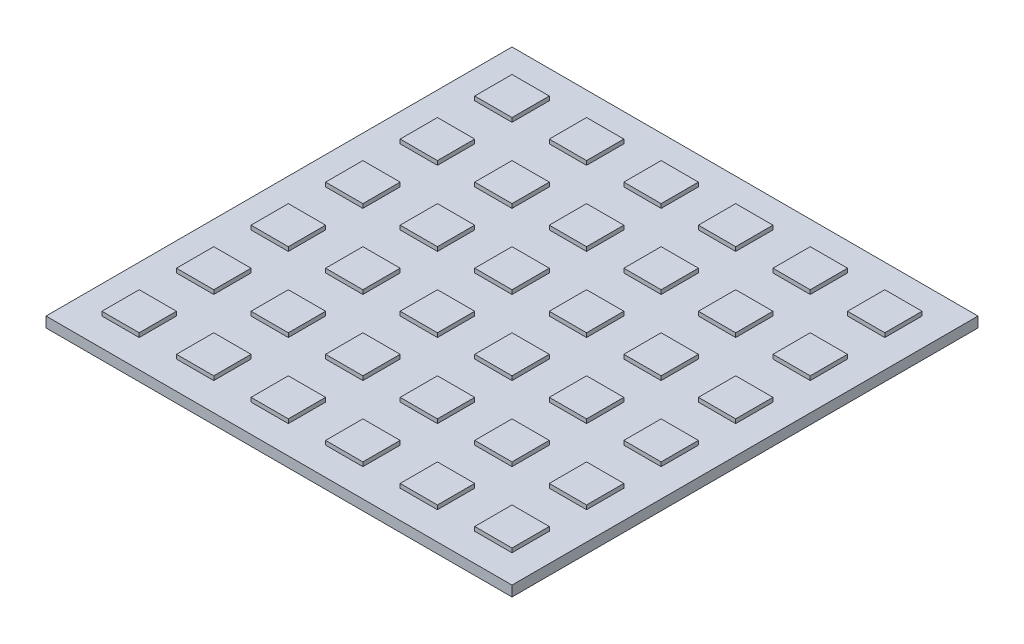
SolidWorks part; units mm, degrees
ref_plane "Front Plane" through (0, 0, 0) normal (0, 0, 1) x (1, 0, 0)
ref_plane "Top Plane" through (0, 0, 0) normal (0, 1, 0) x (1, 0, 0)
ref_plane "Right Plane" through (0, 0, 0) normal (1, 0, 0) x (0, 0, -1)
sketch "Sketch1" plane through (0, 0, 0) normal (0, 1, 0) x (1, 0, 0)
  line L1 (-112.5, 112.5) -> (112.5, 112.5)
  line L2 (-112.5, 112.5) -> (-112.5, -112.5)
  line L3 (-112.5, -112.5) -> (112.5, -112.5)
  line L4 (112.5, 112.5) -> (112.5, -112.5)
  line L5 (-112.5, 112.5) -> (112.5, -112.5) construction
  line L6 (-112.5, -112.5) -> (112.5, 112.5) construction
  point P0 (0, 0)
  dimension "D1" = 225
  dimension "D2" = 225
extrude "Boss-Extrude1" add sketch "Sketch1" along normal blind 5
sketch "Sketch2" plane through (0, 5, 0) normal (0, 1, 0) x (1, 0, 0)
  line L0 (0, 0) -> (0, 112.5) construction
  line L1 (-99, 99) -> (-81, 99)
  line L2 (-99, 99) -> (-99, 81)
  line L3 (-99, 81) -> (-81, 81)
  line L4 (-81, 99) -> (-81, 81)
  line L5 (112.5, 112.5) -> (-112.5, 112.5) construction
  line L6 (-99, 99) -> (-81, 81) construction
  line L7 (-90, 90) -> (0, 90) construction
  dimension "D1" = 18
  dimension "D2" = 18
  dimension "D3" = 90
  dimension "D4" = 90
extrude "Boss-Extrude2" add sketch "Sketch2" along normal blind 2
pattern_linear "LPattern1" count 6 spacing 36 along (1, 0, 0) count 6 spacing 36 along (0, 0, 1) of "Boss-Extrude2"
